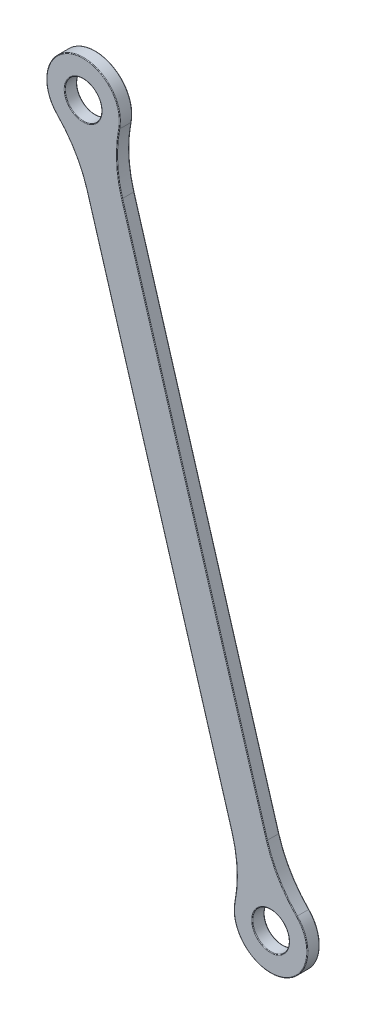
SolidWorks part; units mm, degrees
ref_plane "Front Plane" through (0, 0, 0) normal (0, 0, 1) x (1, 0, 0)
ref_plane "Top Plane" through (0, 0, 0) normal (0, 1, 0) x (1, 0, 0)
ref_plane "Right Plane" through (0, 0, 0) normal (1, 0, 0) x (0, 0, -1)
sketch "Sketch1" plane through (0, 0, 0) normal (0, 0, 1) x (1, 0, 0)
  line L0 (33.7792, 57.2801) -> (-12.1462, 210.5473) construction
  line L1 (33.7792, 57.2801) -> (-12.1462, 210.5473) construction
  line L2 (-12.1462, 210.5473) -> (33.7792, 57.2801) construction
  line L3 (-7.8356, 211.839) -> (38.0898, 58.5717)
  line L4 (-16.4569, 209.2557) -> (29.4685, 55.9884)
  circle A0 centre (33.7792, 57.2801) radius 9
  circle A1 centre (-12.1462, 210.5473) radius 9
  arc A2 (-7.8356, 211.839) -> (-16.4569, 209.2557) centre (-12.1462, 210.5473) ccw
  arc A3 (29.4685, 55.9884) -> (38.0898, 58.5717) centre (33.7792, 57.2801) ccw
  arc A4 (-7.8356, 211.839) -> (-16.4569, 209.2557) centre (-12.1462, 210.5473) cw
  arc A5 (29.4685, 55.9884) -> (38.0898, 58.5717) centre (33.7792, 57.2801) cw
  point P4 (10.8165, 133.9137)
  dimension "D1" = 18
  dimension "D2" = 9
extrude "Boss-Extrude1" add sketch "Sketch1" against normal blind 3 contours A2 L3 A1 L4 | A1 L4 A0 L3 | A3 L4 A0 L3 | L4 A5 L3 A0 | L3 A4 L4 A1
fillet "Fillet1" radius 30 4 edges at (27.2313, 63.4547, -1.5) (-14.2197, 201.7894, -1.5) (-5.5984, 204.3727, -1.5) (35.8526, 66.038, -1.5)
fillet "Fillet2" radius 0.15 20 edges at (-7.6462, 210.5473, -3) (-7.6462, 210.5473, 0) (-14.1463, 198.4849, -3) (-14.1463, 198.4849, 0) (6.5058, 132.622, -3) (6.5058, 132.622, 0) (25.4754, 66.255, -3) (25.4754, 66.255, 0) (36.3625, 48.6588, 0) (36.3625, 48.6588, -3) (35.7792, 69.3425, -3) (35.7792, 69.3425, 0) (15.1271, 135.2053, -3) (15.1271, 135.2053, 0) (-3.8425, 201.5724, -3) (-3.8425, 201.5724, 0) (-14.7295, 219.1686, -3) (-14.7295, 219.1686, 0) (38.2792, 57.2801, -3) (38.2792, 57.2801, 0)
